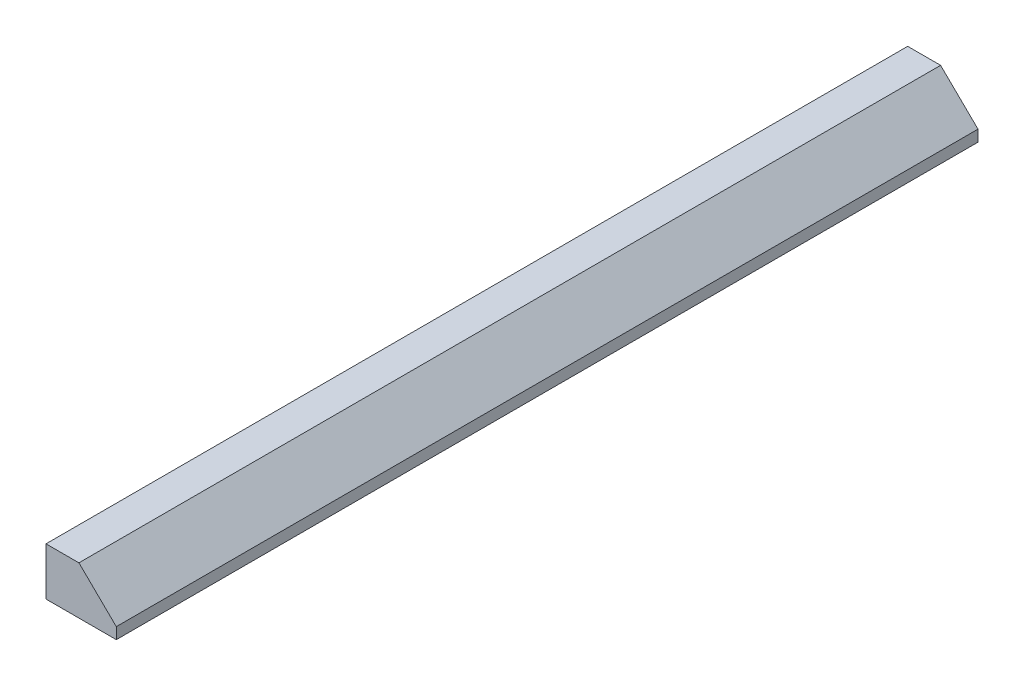
SolidWorks part; units mm, degrees
ref_plane "Front Plane" through (0, 0, 0) normal (0, 0, 1) x (1, 0, 0)
ref_plane "Top Plane" through (0, 0, 0) normal (0, 1, 0) x (1, 0, 0)
ref_plane "Right Plane" through (0, 0, 0) normal (1, 0, 0) x (0, 0, -1)
sketch "Sketch1" plane through (0, 0, 0) normal (0, 0, 1) x (1, 0, 0)
  line L0 (4.2333, 36.8653) -> (83.6083, -40.7458)
  line L1 (-65.6167, 36.8653) -> (4.2333, 36.8653)
  line L2 (-65.6167, 36.8653) -> (-65.6167, -64.7347)
  line L3 (-65.6167, -64.7347) -> (83.6083, -64.7347)
  line L4 (83.6083, -40.7458) -> (83.6083, -64.7347)
  dimension "D1" = 101.6
  dimension "D2" = 149.225
  dimension "D3" = 69.85
extrude "Boss-Extrude1" add sketch "Sketch1" along normal blind 1828.8
sketch "Sketch3" plane through (-65.6167, 0, 0) normal (-1, 0, 0) x (0, 0, 1)
  line L0 (1828.8, -64.7347) -> (0, -64.7347) construction
  line L2 (914.4, -64.7347) -> (914.4, 36.8653) construction
  line L3 (1828.8, 36.8653) -> (0, 36.8653) construction
  circle A0 centre (769.62, -13.9347) radius 8.5725
  circle A1 centre (1059.18, -13.9347) radius 8.5725
  point P2 (914.4, -13.9347)
  dimension "D1" = 17.145
  dimension "D2" = 50.8
  dimension "D3" = 144.78
extrude "Cut-Extrude2" cut sketch "Sketch3" against normal blind 63.5
